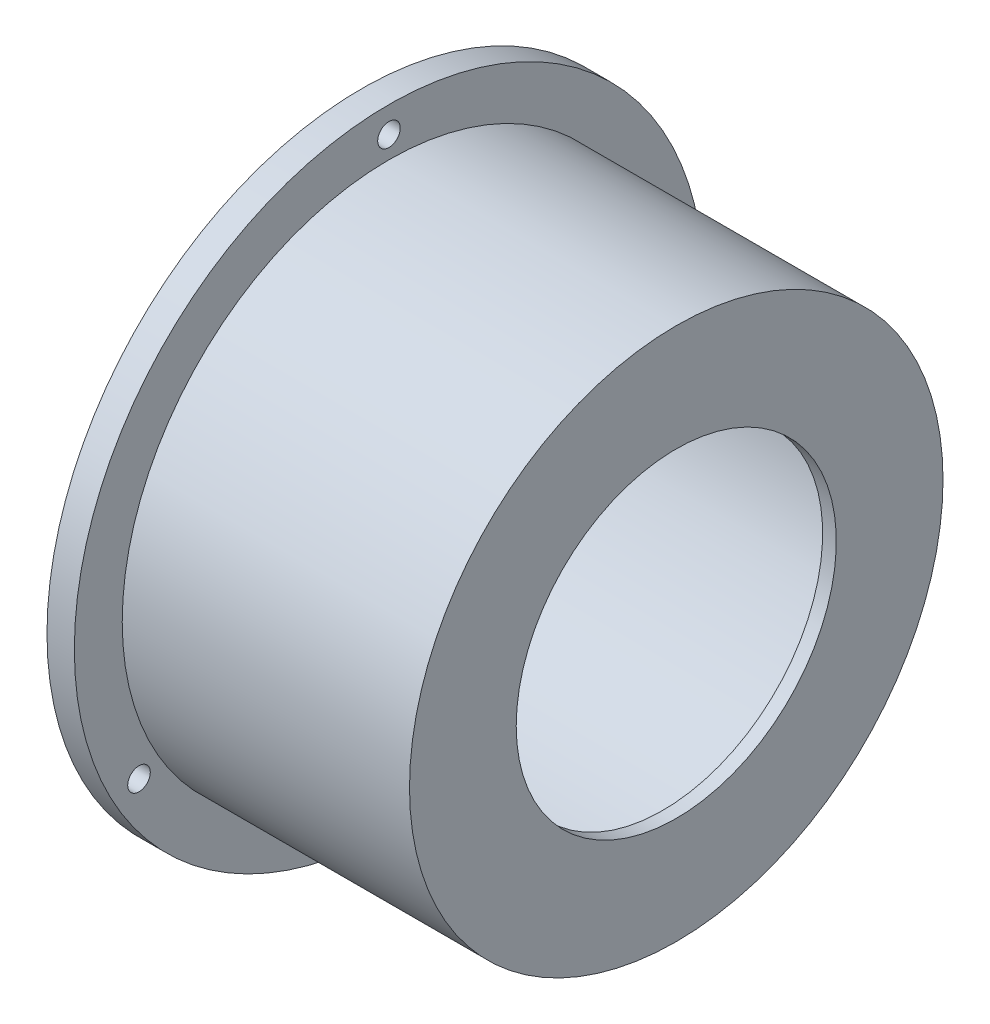
SolidWorks part; units mm, degrees
material "AISI 304"
ref_plane "Front Plane" through (0, 0, 0) normal (0, 0, 1) x (1, 0, 0)
ref_plane "Top Plane" through (0, 0, 0) normal (0, 1, 0) x (1, 0, 0)
ref_plane "Right Plane" through (0, 0, 0) normal (1, 0, 0) x (0, 0, -1)
sketch "Axial profile (mm)" plane through (0, 0, 0) normal (0, 0, 1) x (1, 0, 0)
  line L0 (-110, 0) -> (75, 0) construction
  line L1 (135.7, 36.4) -> (179.7, 36.4)
  line L2 (179.7, 36.4) -> (179.7, 23.4)
  line L3 (179.7, 23.4) -> (181.7, 23.4)
  line L4 (181.7, 23.4) -> (181.7, 39)
  line L5 (181.7, 39) -> (139.7, 39)
  line L6 (139.7, 39) -> (139.7, 46)
  line L7 (139.7, 46) -> (135.7, 46)
  line L8 (135.7, 46) -> (135.7, 36.4)
revolve "Full revolution" add sketch "Axial profile (mm)" angle 360 about L0
sketch "Sketch2" plane through (0, 0, 0) normal (1, 0, 0) x (0, 0, -1)
  circle A0 centre (0, 42.2) radius 1.65
  circle A1 centre (-36.5463, -21.1) radius 1.65
  circle A2 centre (36.5463, -21.1) radius 1.65
extrude "Axial holes" cut sketch "Sketch2" along normal through all and the other way through all
